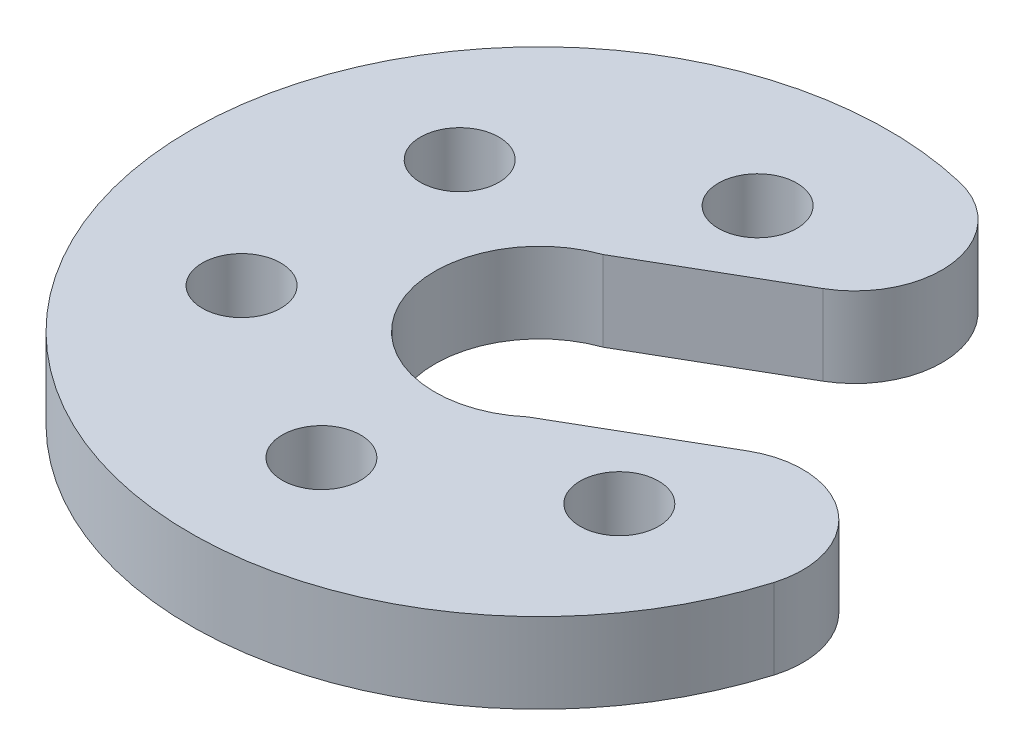
SolidWorks part; units mm, degrees
ref_plane "Front Plane" through (0, 0, 0) normal (0, 0, 1) x (1, 0, 0)
ref_plane "Top Plane" through (0, 0, 0) normal (0, 1, 0) x (1, 0, 0)
ref_plane "Right Plane" through (0, 0, 0) normal (1, 0, 0) x (0, 0, -1)
sketch "Sketch1" plane through (0, 0, 0) normal (0, 1, 0) x (1, 0, 0)
  circle A0 centre (0, 0) radius 20
  circle A1 centre (0, 0) radius 6
  circle A2 centre (0, 12.5) radius 2.25
  circle A3 centre (0, 0) radius 12.5 construction
  circle A4 centre (10.8253, 6.25) radius 2.25
  circle A5 centre (10.8253, -6.25) radius 2.25
  circle A6 centre (0, -12.5) radius 2.25
  circle A7 centre (-10.8253, -6.25) radius 2.25
  circle A8 centre (-10.8253, 6.25) radius 2.25
  point P19 (0, 0)
  dimension "D1" = 12
  dimension "D2" = 40
  dimension "D3" = 4.5
  dimension "D4" = 25
  dimension "D5" = 6
extrude "Boss-Extrude1" add sketch "Sketch1" along normal blind 4.6
sketch "Sketch2" plane through (0, 4.6, 0) normal (0, 1, 0) x (1, 0, 0)
  line L0 (0, 0) -> (10.8253, 6.25) construction
  line L1 (-2.0053, 5.655) -> (13.5997, 14.6645)
  line L2 (3.8947, -4.5641) -> (19.4997, 4.4454)
  arc A0 (3.8947, -4.5641) -> (-2.0053, 5.655) centre (0, 0) ccw
  circle A1 centre (0, 0) radius 6 construction
  circle A4 centre (10.8253, 6.25) radius 2.25 construction
  circle A5 centre (0, 0) radius 20 construction
  dimension "D1" = 11.8
  dimension "D2" = 5.9
extrude "Cut-Extrude1" cut sketch "Sketch2" against normal through all and the other way through all
fillet "Fillet2" radius 5 2 edges at (19.4997, 2.3, -4.4454) (13.5997, 2.3, -14.6645)
